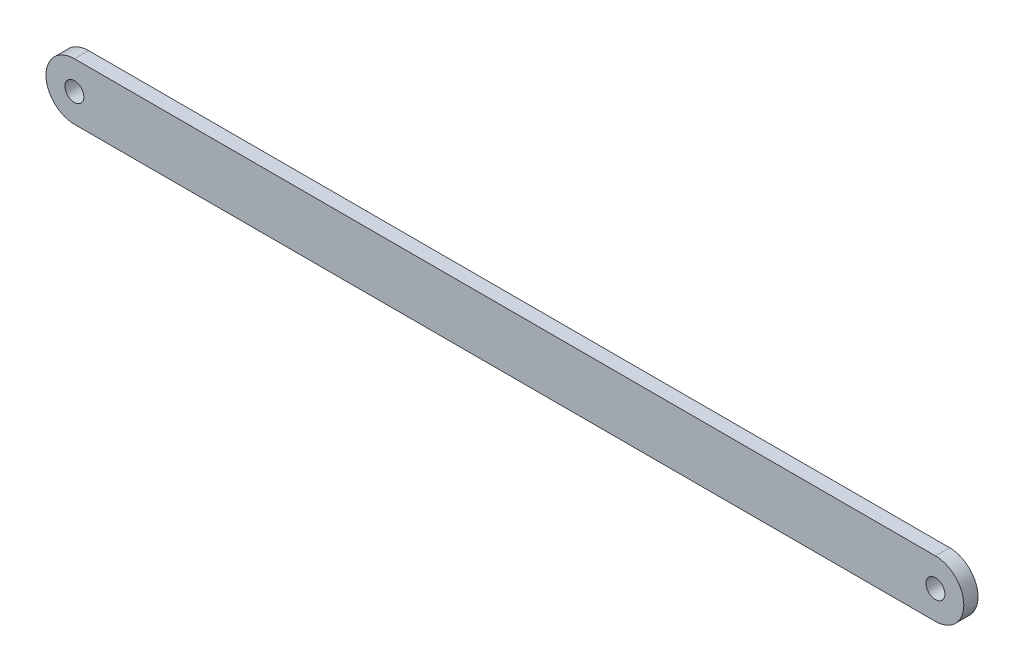
SolidWorks part; units mm, degrees
ref_plane "Front Plane" through (0, 0, 0) normal (0, 0, 1) x (1, 0, 0)
ref_plane "Top Plane" through (0, 0, 0) normal (0, 1, 0) x (1, 0, 0)
ref_plane "Right Plane" through (0, 0, 0) normal (1, 0, 0) x (0, 0, -1)
sketch "Sketch1" plane through (0, 0, 0) normal (0, 0, 1) x (1, 0, 0)
  line L0 (-35.3127, 0) -> (146.6873, 0) construction
  line L1 (-35.3127, 6) -> (146.6873, 6)
  line L2 (-35.3127, -6) -> (146.6873, -6)
  arc A0 (-35.3127, 6) -> (-35.3127, -6) centre (-35.3127, 0) ccw
  arc A1 (146.6873, -6) -> (146.6873, 6) centre (146.6873, 0) ccw
  circle A2 centre (-35.3127, 0) radius 2
  circle A3 centre (146.6873, 0) radius 2
  point P3 (55.6873, 0)
  dimension "D3" = 4
  dimension "D4" = 4
  dimension "D1" = 182
  dimension "D2" = 12
extrude "Boss-Extrude3" add sketch "Sketch1" along normal blind 3
